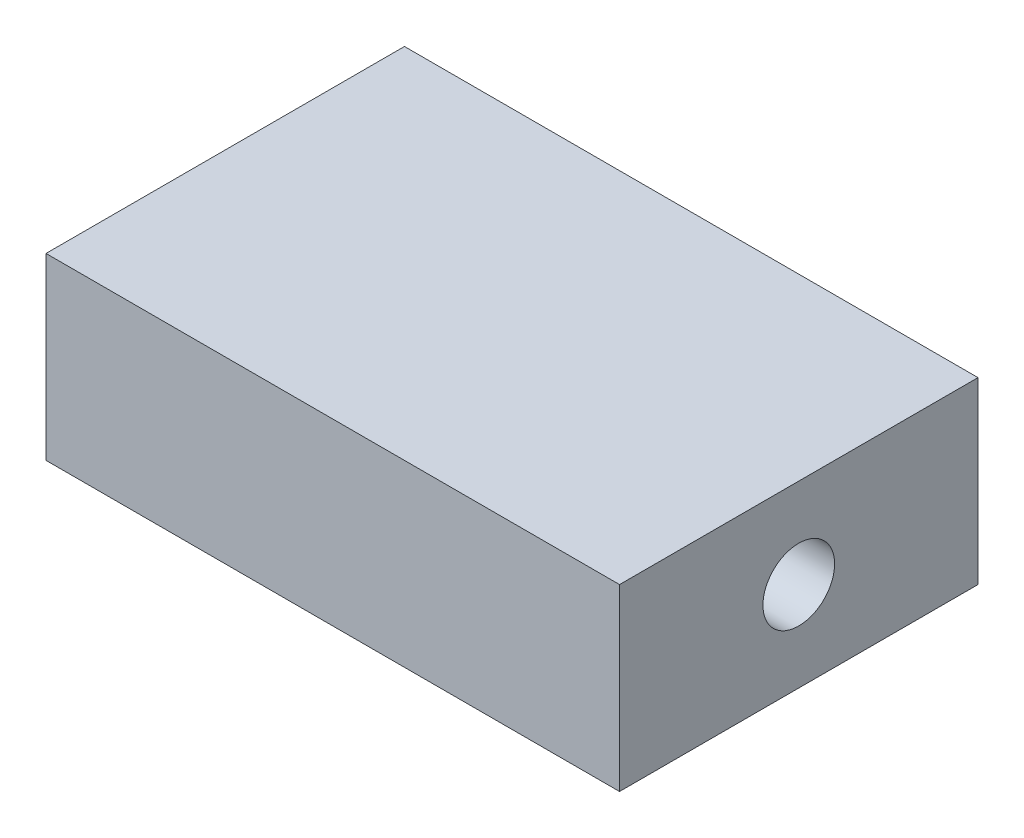
SolidWorks part; units mm, degrees
ref_plane "Front Plane" through (0, 0, 0) normal (0, 0, 1) x (1, 0, 0)
ref_plane "Top Plane" through (0, 0, 0) normal (0, 1, 0) x (1, 0, 0)
ref_plane "Right Plane" through (0, 0, 0) normal (1, 0, 0) x (0, 0, -1)
sketch "Sketch1" plane through (0, 0, 0) normal (0, 1, 0) x (1, 0, 0)
  line L1 (-40, -25) -> (40, -25)
  line L2 (-40, -25) -> (-40, 25)
  line L3 (-40, 25) -> (40, 25)
  line L4 (40, -25) -> (40, 25)
  line L5 (-40, -25) -> (40, 25) construction
  line L6 (-40, 25) -> (40, -25) construction
  point P0 (0, 0)
  dimension "D1" = 50
  dimension "D2" = 80
extrude "Boss-Extrude1" add sketch "Sketch1" along normal blind 25
sketch "Sketch2" plane through (0, 0, 0) normal (1, 0, 0) x (0, 0, -1)
  line L0 (0, 13.75) -> (0, -13.75) construction
  line L1 (-25, 25) -> (-25, 0) construction
  circle A0 centre (0, 12.5) radius 5
  point P8 (-25, 12.5)
  dimension "D1" = 10
extrude "Cut-Extrude1" cut sketch "Sketch2" against normal through all both and the other way through all
